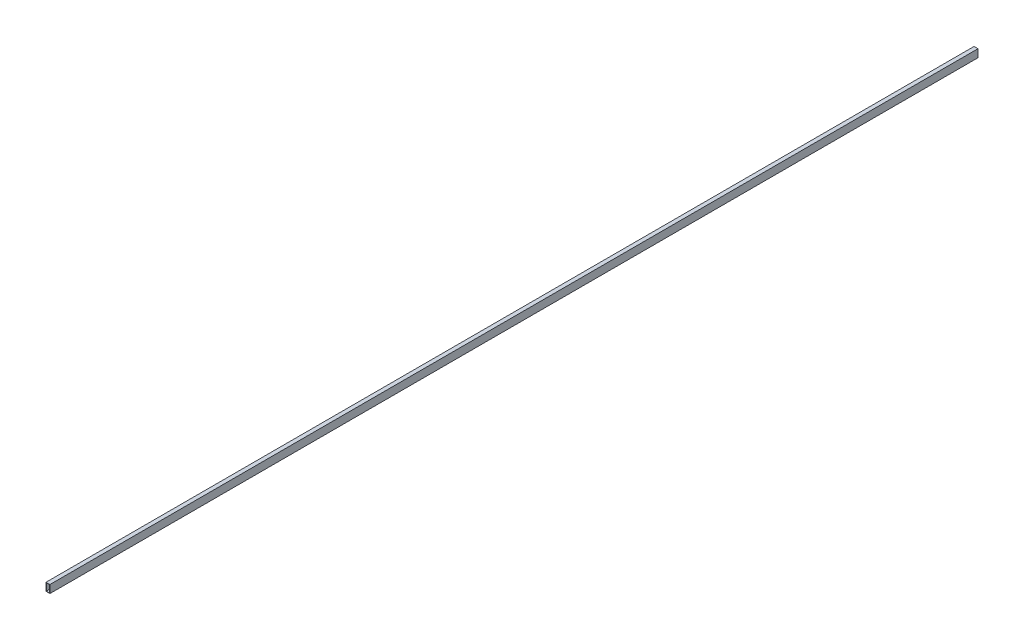
SolidWorks part; units mm, degrees
ref_plane "Alzado" through (0, 0, 0) normal (0, 0, 1) x (1, 0, 0)
ref_plane "Planta" through (0, 0, 0) normal (0, 1, 0) x (1, 0, 0)
ref_plane "Vista lateral" through (0, 0, 0) normal (1, 0, 0) x (0, 0, -1)
sketch "Croquis1" plane through (0, 0, 0) normal (0, 0, 1) x (1, 0, 0)
  line L0 (10.81, -23.51) -> (10.81, 23.51)
  line L1 (-12.7, -25.4) -> (12.7, -25.4)
  line L2 (-12.7, -25.4) -> (-12.7, 25.4)
  line L3 (-12.7, 25.4) -> (12.7, 25.4)
  line L4 (12.7, -25.4) -> (12.7, 25.4)
  line L5 (-12.7, -25.4) -> (12.7, 25.4) construction
  line L6 (-12.7, 25.4) -> (12.7, -25.4) construction
  line L7 (-10.81, 23.51) -> (10.81, 23.51)
  line L8 (-10.81, -23.51) -> (-10.81, 23.51)
  line L9 (-10.81, -23.51) -> (10.81, -23.51)
  point P0 (0, 0)
  dimension "D1" = 50.8
  dimension "D2" = 25.4
  dimension "D3" = 1.89
extrude "Saliente-Extruir1" add sketch "Croquis1" along normal blind 6000
